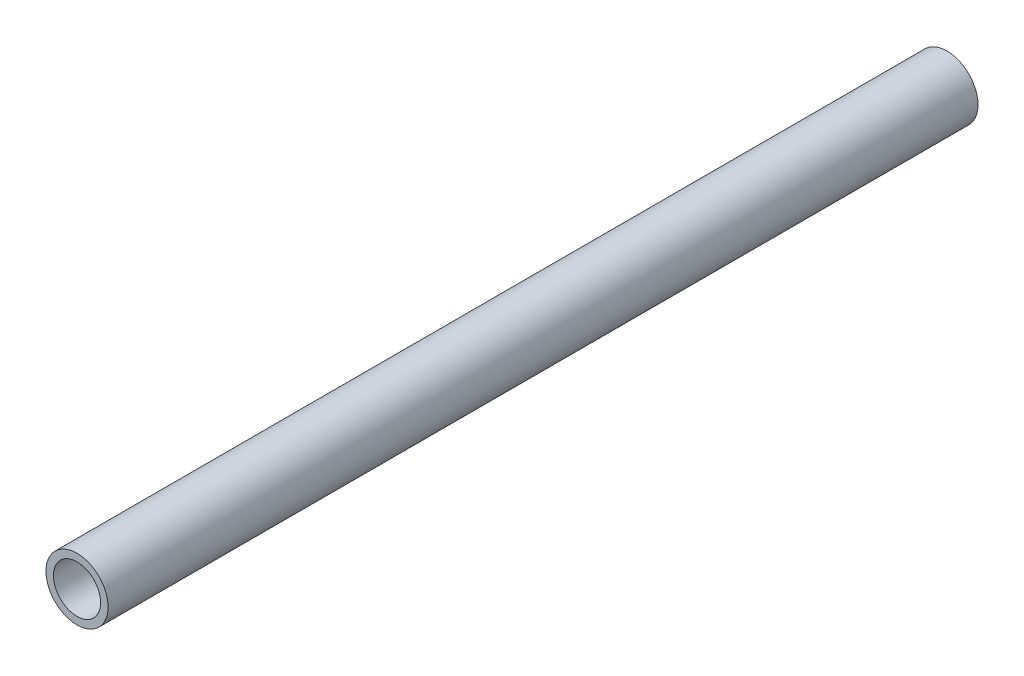
SolidWorks part; units mm, degrees
ref_plane "Front Plane" through (0, 0, 0) normal (0, 0, 1) x (1, 0, 0)
ref_plane "Top Plane" through (0, 0, 0) normal (0, 1, 0) x (1, 0, 0)
ref_plane "Right Plane" through (0, 0, 0) normal (1, 0, 0) x (0, 0, -1)
sketch "Sketch1" plane through (0, 0, 0) normal (0, 0, 1) x (1, 0, 0)
  circle A0 centre (0, 0) radius 12.5
  dimension "D1" = 25
extrude "Extrude-Thin1" add sketch "Sketch1" along normal mid plane 350 thin thin type one direction reverse wall 3
